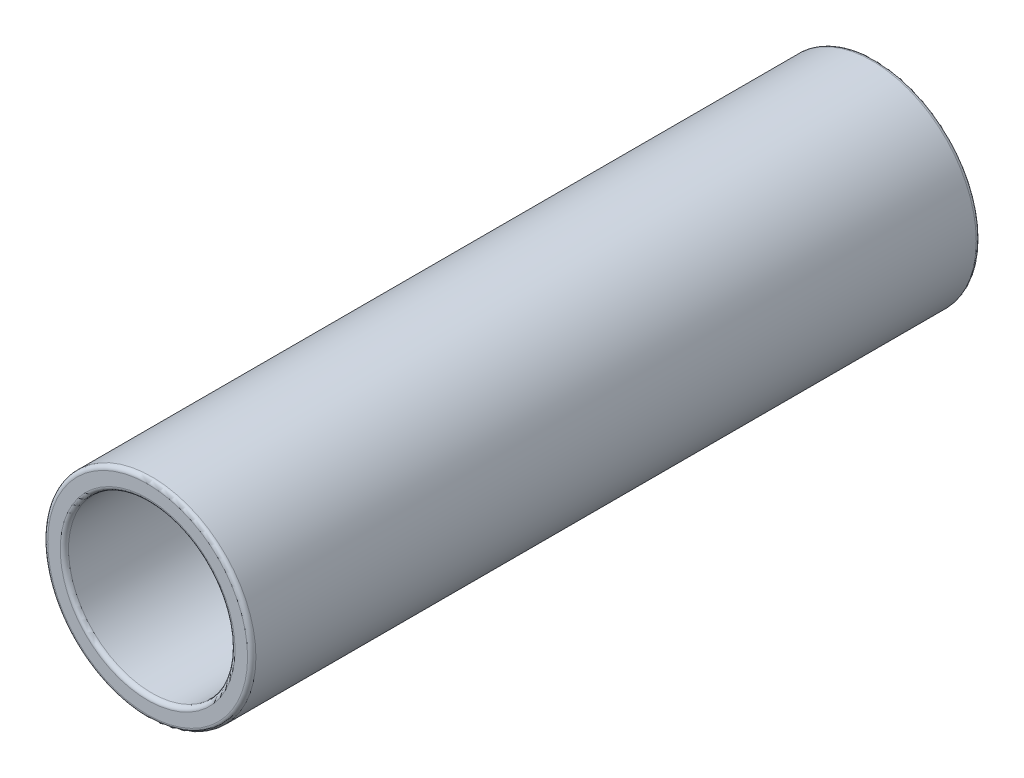
SolidWorks part; units mm, degrees
material "6061 Legierung"
ref_plane "Ebene vorne" through (0, 0, 0) normal (0, 0, 1) x (1, 0, 0)
ref_plane "Ebene oben" through (0, 0, 0) normal (0, 1, 0) x (1, 0, 0)
ref_plane "Ebene rechts" through (0, 0, 0) normal (1, 0, 0) x (0, 0, -1)
sketch "Skizze1" plane through (0, 0, 0) normal (0, 0, 1) x (1, 0, 0)
  circle A0 centre (0, 0) radius 5
  circle A1 centre (0, 0) radius 4
  dimension "D1" = 8
  dimension "D2" = 10
extrude "Aufsatz-Linear austragen1" add sketch "Skizze1" along normal blind 35
fillet "Verrundung1" radius 0.2 4 edges at (4, 0, 0) (5, 0, 0) (4, 0, 35) (5, 0, 35)
